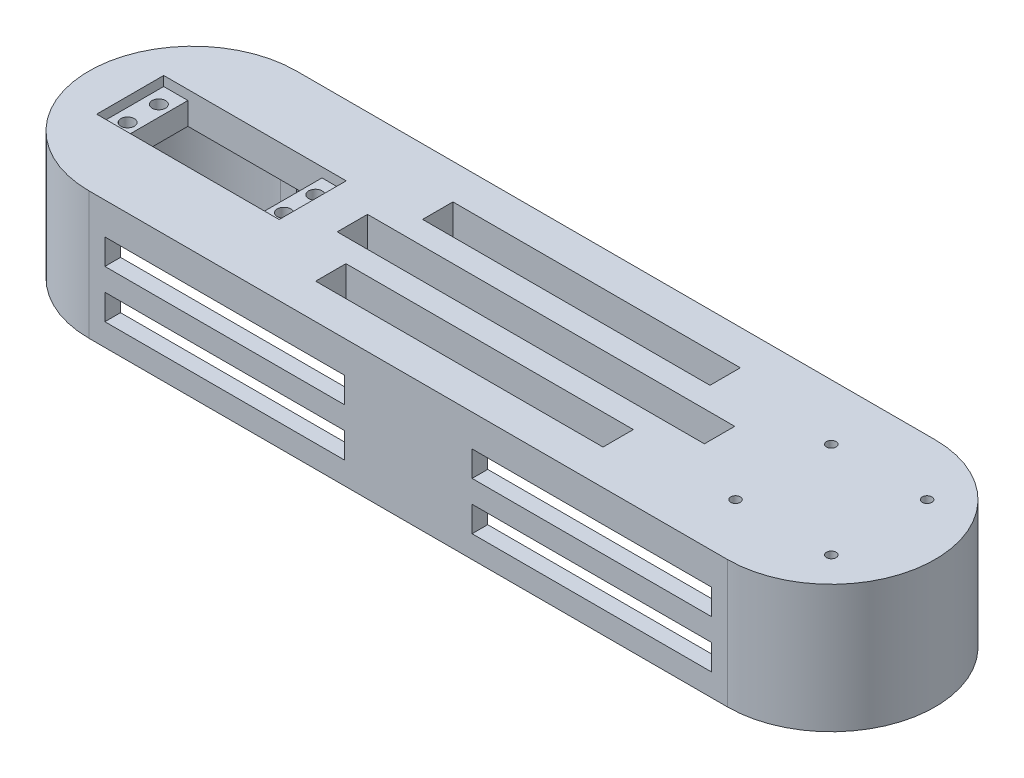
SolidWorks part; units mm, degrees
ref_plane "Front Plane" through (0, 0, 0) normal (0, 0, 1) x (1, 0, 0)
ref_plane "Top Plane" through (0, 0, 0) normal (0, 1, 0) x (1, 0, 0)
ref_plane "Right Plane" through (0, 0, 0) normal (1, 0, 0) x (0, 0, -1)
sketch "Sketch1" plane through (0, 0, 0) normal (0, 1, 0) x (1, 0, 0)
  line L0 (-100, 32.5) -> (100, 32.5)
  line L1 (-100, -32.5) -> (100, -32.5)
  line L2 (-112, 10.5) -> (-70, 10.5)
  line L3 (-70, 10.5) -> (-70, -10.5)
  line L4 (-70, -10.5) -> (-112, -10.5)
  line L5 (-112, -10.5) -> (-112, 10.5)
  line L6 (0, 21.5) -> (-40, 21.5)
  line L7 (-40, 21.5) -> (-40, 12)
  line L8 (-40, 12) -> (0, 12)
  line L9 (0, 12) -> (50, 12)
  line L10 (50, 12) -> (50, 21.5)
  line L11 (50, 21.5) -> (0, 21.5)
  line L12 (-50, 4.75) -> (0, 4.75)
  line L13 (0, 4.75) -> (65, 4.75)
  line L14 (65, 4.75) -> (65, -4.75)
  line L15 (65, -4.75) -> (0, -4.75)
  line L16 (0, -4.75) -> (-50, -4.75)
  line L17 (-50, -4.75) -> (-50, 4.75)
  line L21 (0, -12) -> (-40, -12)
  line L22 (-40, -12) -> (-40, -21.5)
  line L23 (-40, -21.5) -> (0, -21.5)
  line L24 (0, -21.5) -> (50, -21.5)
  line L25 (50, -21.5) -> (50, -12)
  line L26 (50, -12) -> (0, -12)
  line L27 (100, 13.6373) -> (100, -13.3202) construction
  line L28 (82.1775, 0) -> (117.959, 0) construction
  arc A0 (100, 32.5) -> (100, -32.5) centre (100, 0) cw
  arc A1 (-100, 32.5) -> (-100, -32.5) centre (-100, 0) ccw
  circle A6 centre (-115.5, 4.9) radius 2.1
  circle A7 centre (-115.5, -4.9) radius 2.1
  circle A8 centre (-66.5, -4.9) radius 2.1
  circle A9 centre (-66.5, 4.9) radius 2.1
  circle A10 centre (85, 15) radius 1.5
  circle A11 centre (115, 15) radius 1.5
  circle A12 centre (85, -15) radius 1.5
  circle A13 centre (115, -15) radius 1.5
  dimension "D5" = 3
  dimension "D6" = 15
  dimension "D7" = 4.75
  dimension "D8" = 15
  dimension "D9" = 30
  dimension "D11" = 4.2
  dimension "D12" = 4.2
  dimension "D13" = 4.2
  dimension "D14" = 4.2
  dimension "D15" = 3.5
  dimension "D16" = 3.5
  dimension "D17" = 3.5
  dimension "D18" = 3.5
  dimension "D21" = 4.9
  dimension "D22" = 4.9
  dimension "D23" = 4.9
  dimension "D24" = 4.9
  dimension "D1" = 32.5
  dimension "D2" = 32.5
  dimension "D3" = 100
  dimension "D4" = 100
  dimension "D10" = 12
  dimension "D19" = 10.5
  dimension "D20" = 10.5
  dimension "D25" = 9.5
  dimension "D26" = 9.5
  dimension "D27" = 9.5
  dimension "D28" = 50
  dimension "D29" = 0
  dimension "D30" = 0
  dimension "D31" = 40
  dimension "D32" = 65
  dimension "D33" = 0
  dimension "D34" = 0
  dimension "D35" = 50
  dimension "D36" = 40
  dimension "D37" = 0
  dimension "D38" = 0
  dimension "D39" = 50
  dimension "D40" = 11
  dimension "D41" = 11
extrude "Boss-Extrude1" add sketch "Sketch1" along normal blind 10
sketch "Sketch2" plane through (0, 0, 0) normal (0, 1, 0) x (1, 0, 0)
  line L0 (-100, 32.5) -> (100, 32.5)
  line L1 (100, -32.5) -> (-100, -32.5)
  line L4 (99.6685, 27.511) -> (-100, 27.511)
  line L5 (-100, -27.6007) -> (100.9985, -27.6007)
  arc A0 (100, 32.5) -> (100, -32.5) centre (100, 0) cw
  arc A1 (-100, 32.5) -> (-100, -32.5) centre (-100, 0) ccw
  arc A3 (99.6685, 27.511) -> (100.9985, -27.6007) centre (100.9985, -0.0288) cw
  arc A4 (-100, 27.511) -> (-100, -27.6007) centre (-100, -0.0449) ccw
  dimension "D3" = 5
  dimension "D4" = 5
extrude "Boss-Extrude2" add sketch "Sketch2" against normal blind 30
sketch "Sketch3" plane through (0, 0, 0) normal (0, 0, 1) x (1, 0, 0)
  line L7 (-95, -23) -> (-95, -15)
  line L10 (95, -15) -> (95, -23)
  line L24 (95, 0) -> (95, -8)
  line L27 (-95, -8) -> (-95, 0)
  line L28 (-20, 0) -> (-95, 0)
  line L29 (-95, -8) -> (-20, -8)
  line L30 (-20, -8) -> (-20, 0)
  line L31 (-95, -23) -> (-20, -23)
  line L32 (-20, -23) -> (-20, -15)
  line L33 (-20, -15) -> (-95, -15)
  line L34 (20, 0) -> (20, -8)
  line L35 (20, -8) -> (95, -8)
  line L36 (95, 0) -> (20, 0)
  line L37 (20, -15) -> (20, -23)
  line L38 (20, -23) -> (95, -23)
  line L39 (95, -15) -> (20, -15)
  line L40 (100, 10) -> (100, -30) construction
  line L41 (-100, 10) -> (-100, -30) construction
  line L42 (-100, 10) -> (100, 10) construction
  line L43 (-100, -30) -> (100, -30) construction
  point P16 (-20, -4)
  point P20 (95, -19)
  point P23 (-95, -4)
  dimension "D1" = 8
  dimension "D2" = 8
  dimension "D3" = 20
  dimension "D4" = 20
  dimension "D5" = 0
  dimension "D6" = 5
  dimension "D7" = 0
  dimension "D8" = 5
  dimension "D9" = 0
  dimension "D10" = 10
  dimension "D11" = 7
  dimension "D12" = 7
  dimension "D13" = 8
  dimension "D14" = 8
  dimension "D15" = 10
extrude "Cut-Extrude1" cut sketch "Sketch3" against normal mid plane 90
sketch "Sketch4" plane through (0, 10, 0) normal (0, 1, 0) x (1, 0, 0)
  line L0 (-112, -10.5) -> (-70, -10.5) construction
  line L1 (-112, -10.5) -> (-119.58, -10.5)
  line L2 (-112, -10.5) -> (-112, 10.5)
  line L3 (-112, 10.5) -> (-119.58, 10.5)
  line L4 (-119.58, -10.5) -> (-119.58, 10.5)
  line L5 (-70, 10.5) -> (-62.42, 10.5)
  line L6 (-70, 10.5) -> (-70, -10.5)
  line L7 (-70, -10.5) -> (-62.42, -10.5)
  line L8 (-62.42, 10.5) -> (-62.42, -10.5)
  line L9 (-70, 10.5) -> (-112, 10.5) construction
  dimension "D1" = 0
  dimension "D2" = 0
  dimension "D3" = 7.58
  dimension "D4" = 7.58
extrude "Cut-Extrude2" cut sketch "Sketch4" against normal blind 3
